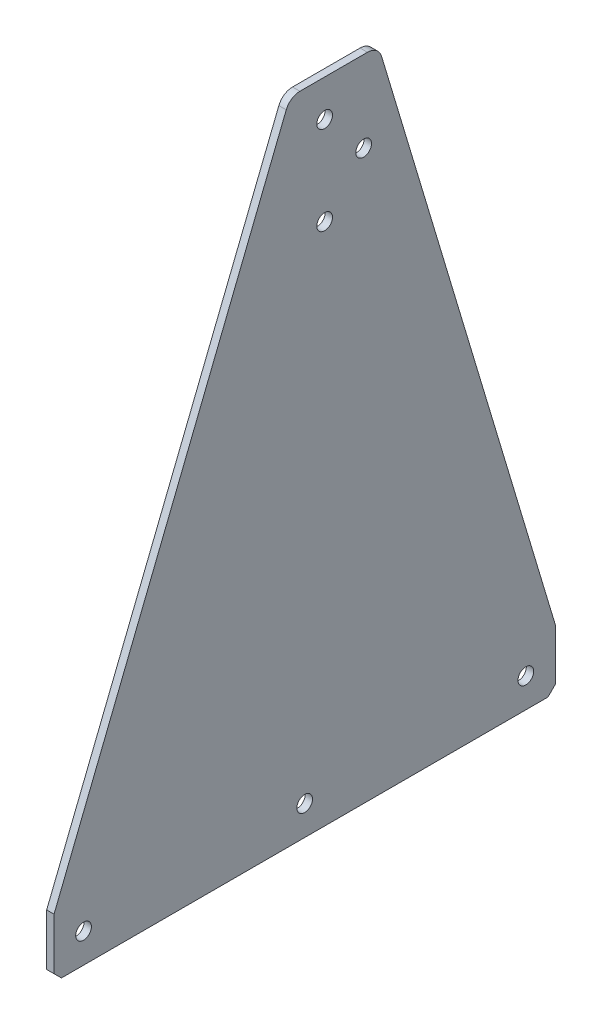
SolidWorks part; units mm, degrees
material "6061-T6 (SS)"
ref_plane "Front Plane" through (0, 0, 0) normal (0, 0, 1) x (1, 0, 0)
ref_plane "Top Plane" through (0, 0, 0) normal (0, 1, 0) x (1, 0, 0)
ref_plane "Right Plane" through (0, 0, 0) normal (1, 0, 0) x (0, 0, -1)
sketch "Sketch1" plane through (0, 0, 0) normal (1, 0, 0) x (0, 0, -1)
  line L1 (105.8992, 279.4) -> (134.9754, 279.4)
  line L2 (141.0576, 274.8747) -> (215.9, 25.4)
  line L3 (215.9, 25.4) -> (215.9, 0)
  line L4 (215.9, 0) -> (0, 0)
  line L5 (0, 25.4) -> (0, 0)
  line L6 (100.0033, 275.4083) -> (0, 25.4)
  arc A0 (100.0033, 275.4083) -> (105.8992, 279.4) centre (105.8992, 273.05) cw
  arc A1 (134.9754, 279.4) -> (141.0576, 274.8747) centre (134.9754, 273.05) cw
  point P2 (101.6, 279.4)
  point P12 (139.7, 279.4)
  dimension "D4" = 6.35
  dimension "D1" = 101.6
  dimension "D2" = 279.4
  dimension "D3" = 215.9
  dimension "D5" = 25.4
  dimension "D6" = 76.2
extrude "Boss-Extrude1" add sketch "Sketch1" along normal blind 3.175
sketch "Sketch2" [suppressed] plane through (3.175, 0, 0) normal (1, 0, 0) x (0, 0, -1)
  line L0 (-279.4, 0) -> (279.4, 0) construction
  line L1 (254, 0) -> (228.6, 0)
  line L2 (254, 0) -> (254, 19.05)
  line L3 (247.65, 25.4) -> (234.95, 25.4)
  line L4 (228.6, 0) -> (228.6, 19.05)
  line L6 (203.2, 0) -> (177.8, 0)
  line L7 (203.2, 0) -> (203.2, 19.05)
  line L8 (196.85, 25.4) -> (184.15, 25.4)
  line L9 (177.8, 0) -> (177.8, 19.05)
  line L10 (152.4, 0) -> (127, 0)
  line L11 (152.4, 0) -> (152.4, 19.05)
  line L12 (146.05, 25.4) -> (133.35, 25.4)
  line L13 (127, 0) -> (127, 19.05)
  line L14 (101.6, 0) -> (76.2, 0)
  line L15 (101.6, 0) -> (101.6, 19.05)
  line L16 (95.25, 25.4) -> (82.55, 25.4)
  line L17 (76.2, 0) -> (76.2, 19.05)
  line L18 (50.8, 0) -> (25.4, 0)
  line L19 (50.8, 0) -> (50.8, 19.05)
  line L20 (44.45, 25.4) -> (31.75, 25.4)
  line L21 (25.4, 0) -> (25.4, 19.05)
  line L22 (50.8, 0) -> (76.2, 0) construction
  line L23 (101.6, 0) -> (127, 0) construction
  line L24 (152.4, 0) -> (177.8, 0) construction
  line L25 (203.2, 0) -> (228.6, 0) construction
  line L27 (279.4, 0) -> (279.4, 12.7) construction
  line L28 (0, 609.6) -> (0, 0) construction
  arc A0 (31.75, 25.4) -> (25.4, 19.05) centre (31.75, 19.05) ccw
  arc A1 (50.8, 19.05) -> (44.45, 25.4) centre (44.45, 19.05) ccw
  arc A2 (82.55, 25.4) -> (76.2, 19.05) centre (82.55, 19.05) ccw
  arc A3 (101.6, 19.05) -> (95.25, 25.4) centre (95.25, 19.05) ccw
  arc A4 (133.35, 25.4) -> (127, 19.05) centre (133.35, 19.05) ccw
  arc A5 (152.4, 19.05) -> (146.05, 25.4) centre (146.05, 19.05) ccw
  arc A6 (184.15, 25.4) -> (177.8, 19.05) centre (184.15, 19.05) ccw
  arc A7 (203.2, 19.05) -> (196.85, 25.4) centre (196.85, 19.05) ccw
  arc A8 (234.95, 25.4) -> (228.6, 19.05) centre (234.95, 19.05) ccw
  arc A9 (254, 19.05) -> (247.65, 25.4) centre (247.65, 19.05) ccw
  point P52 (254, 25.4)
  dimension "D5" = 6.35
  dimension "D1" = 25.4
  dimension "D2" = 25.4
  dimension "D3" = 25.4
  dimension "D4" = 25.4
extrude "Cut-Extrude1" [suppressed] cut sketch "Sketch2" against normal through all
sketch "Sketch3" plane through (3.175, 0, 0) normal (1, 0, 0) x (0, 0, -1)
  line L0 (0, 0) -> (215.9, 0) construction
  line L3 (215.9, 0) -> (215.9, 25.4) construction
  circle A0 centre (133.35, 244.475) radius 3.3782
  circle A1 centre (116.5495, 225.425) radius 3.3782
  circle A2 centre (116.5495, 263.525) radius 3.3782
  dimension "D1" = 6.7564
  dimension "D2" = 244.475
  dimension "D3" = 82.55
  dimension "D4" = 25.4
  dimension "D5" = 25.4
  dimension "D6" = 38.1
extrude "Cut-Extrude2" cut sketch "Sketch3" against normal through all
sketch "Sketch4" plane through (3.175, 0, 0) normal (1, 0, 0) x (0, 0, -1)
  line L0 (0, 0) -> (215.9, 0) construction
  line L1 (0, 25.4) -> (0, 0) construction
  line L2 (215.9, 0) -> (215.9, 25.4) construction
  line L3 (12.7, 12.7) -> (203.2, 12.7) construction
  circle A0 centre (12.7, 12.7) radius 3.3782
  circle A1 centre (107.95, 12.7) radius 3.3782
  circle A2 centre (203.2, 12.7) radius 3.3782
  point P6 (0, 0)
  dimension "D1" = 12.7
  dimension "D2" = 12.7
  dimension "D3" = 12.7
  dimension "D4" = 6.7564
extrude "Cut-Extrude3" cut sketch "Sketch4" against normal through all
chamfer "Chamfer1" distance 3.175 angle 45 2 edges at (1.5875, 0, 0) (1.5875, 0, -215.9)
